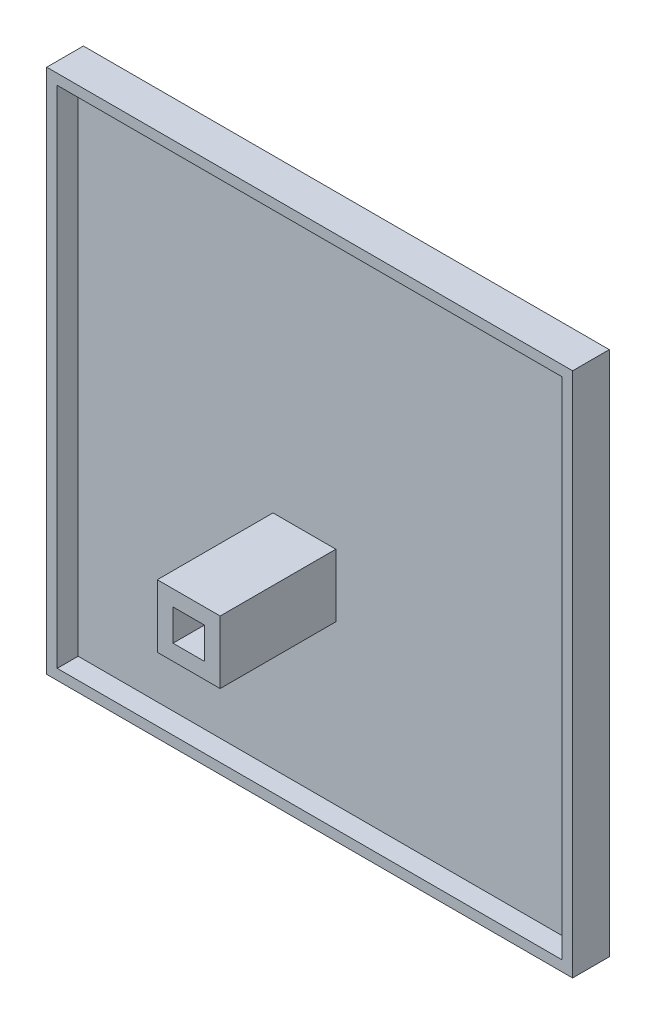
SolidWorks part; units mm, degrees
other "標示1"
sketch "草圖9" plane through (100.4, -100.4, 24.09) normal (0.0686, -0.0814, 0.9943) x (0.9976, 0.0176, -0.0674)
ref_plane "前基準面" through (0, 0, 0) normal (0, 0, 1) x (1, 0, 0)
ref_plane "上基準面" through (0, 0, 0) normal (0, 1, 0) x (1, 0, 0)
ref_plane "右基準面" through (0, 0, 0) normal (1, 0, 0) x (0, 0, -1)
sketch "草圖1" plane through (0, 0, 0) normal (0, 0, 1) x (1, 0, 0)
  line L1 (0, 0) -> (100.4, 0)
  line L2 (0, 0) -> (0, -100.4)
  line L3 (0, -100.4) -> (100.4, -100.4)
  line L4 (100.4, 0) -> (100.4, -100.4)
  dimension "D1" = 100.4
  dimension "D2" = 100.4
extrude "填料-伸長2" add sketch "草圖1" along normal blind 2 contours L1 L4 L3 L2
sketch "草圖2" plane through (0, 0, 2) normal (0, 0, 1) x (1, 0, 0)
  line L0 (0, 0) -> (0, -100.4) construction
  line L1 (100.4, 0) -> (0, 0)
  line L2 (100.4, 0) -> (100.4, -2)
  line L3 (100.4, -2) -> (0, -2)
  line L4 (0, 0) -> (0, -2)
  line L6 (0, -2) -> (1, -2)
  line L11 (100.4, -2) -> (55.6, -2)
  line L23 (100.4, -100.4) -> (0, -100.4)
  line L24 (100.4, -100.4) -> (100.4, -98.4)
  line L25 (100.4, -98.4) -> (0, -98.4)
  line L26 (0, -100.4) -> (0, -98.4)
  line M4 (0, 0) -> (0, -100.4)
  line M5 (0, -100.4) -> (100.4, -100.4)
  line M6 (100.4, -100.4) -> (100.4, 0)
  line M7 (100.4, 0) -> (0, 0)
  dimension "D1" = 2
  dimension "D2" = 2
extrude "填料-伸長3" add sketch "草圖2" along normal blind 4 contours L3 M6 M7 M4 | L25 M6 M4 M5
sketch "草圖3" plane through (0, 0, 2) normal (0, 0, 1) x (1, 0, 0)
  line L0 (0, -2) -> (0, -98.4) construction
  line L1 (0, -2) -> (2, -2)
  line L2 (0, -2) -> (0, -98.4)
  line L3 (0, -98.4) -> (2, -98.4)
  line L4 (2, -2) -> (2, -98.4)
  line L5 (100.4, -2) -> (0, -2) construction
  line L6 (100.4, -98.4) -> (0, -98.4) construction
  line L8 (100.4, -2) -> (98.4, -2)
  line L9 (100.4, -2) -> (100.4, -98.4)
  line L10 (100.4, -98.4) -> (98.4, -98.4)
  line L11 (98.4, -2) -> (98.4, -98.4)
  dimension "D1" = 2
  dimension "D2" = 2
extrude "填料-伸長4" add sketch "草圖3" along normal blind 4
sketch "草圖4" plane through (0, 0, 2) normal (0, 0, 1) x (1, 0, 0)
  line L1 (39.2, -56.1) -> (51.2, -56.1)
  line L2 (39.2, -56.1) -> (39.2, -68.1)
  line L3 (39.2, -68.1) -> (51.2, -68.1)
  line L4 (51.2, -56.1) -> (51.2, -68.1)
  line L8 (98.4, -2) -> (2, -2) construction
  line L9 (2, -98.4) -> (2, -2) construction
  dimension "D1" = 54.1
  dimension "D2" = 12
  dimension "D3" = 12
  dimension "D4" = 37.2
extrude "填料-伸長5" add sketch "草圖4" along normal blind 22.09
sketch "草圖7" plane through (0, 0, 24.09) normal (0, 0, 1) x (1, 0, 0)
  line L0 (51.2, -56.1) -> (39.2, -56.1) construction
  line L1 (42.2, -59.1) -> (48.2, -59.1)
  line L2 (42.2, -59.1) -> (42.2, -65.1)
  line L3 (42.2, -65.1) -> (48.2, -65.1)
  line L4 (48.2, -59.1) -> (48.2, -65.1)
  line L5 (51.2, -68.1) -> (51.2, -56.1) construction
  dimension "D1" = 6
  dimension "D2" = 6
  dimension "D3" = 3
  dimension "D4" = 3
extrude "除料-伸長1" cut sketch "草圖7" against normal blind 22.09
sketch "草圖8" plane through (0, 0, 2) normal (0, 0, 1) x (1, 0, 0)
  line L1 (48.2, -59.1) -> (42.2, -59.1)
  line L2 (48.2, -59.1) -> (48.2, -65.1)
  line L3 (48.2, -65.1) -> (42.2, -65.1)
  line L4 (42.2, -59.1) -> (42.2, -65.1)
extrude "填料-伸長6" add sketch "草圖8" along normal blind 2
sketch "草圖10" plane through (0, 0, 0) normal (0, 0, -1) x (-1, 0, 0)
  line L1 (0, 0) -> (-100.4, 0)
  line L2 (0, 0) -> (0, -100.4)
  line L3 (0, -100.4) -> (-100.4, -100.4)
  line L4 (-100.4, 0) -> (-100.4, -100.4)
extrude "填料-伸長7" add sketch "草圖10" along normal blind 1
